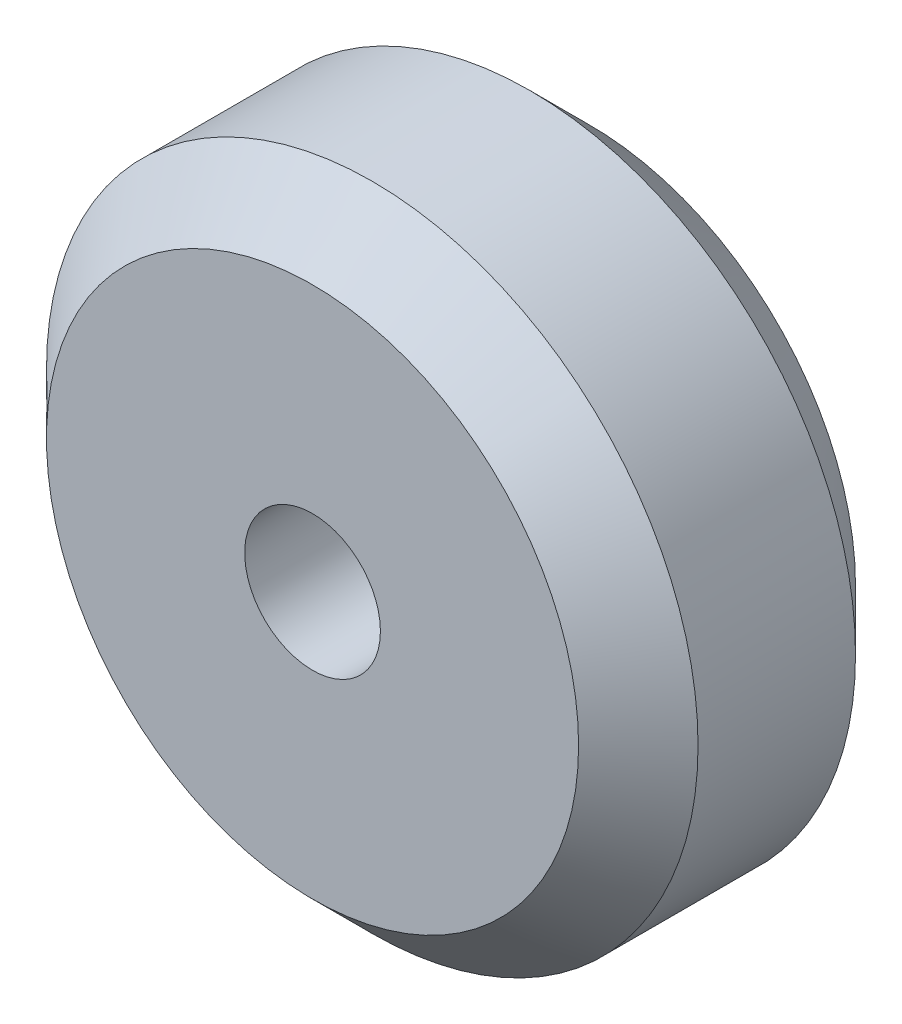
SolidWorks part; units mm, degrees
ref_plane "前视基准面" through (0, 0, 0) normal (0, 0, 1) x (1, 0, 0)
ref_plane "上视基准面" through (0, 0, 0) normal (0, 1, 0) x (1, 0, 0)
ref_plane "右视基准面" through (0, 0, 0) normal (1, 0, 0) x (0, 0, -1)
sketch "草图1" plane through (0, 0, 0) normal (0, 0, 1) x (1, 0, 0)
  circle A0 centre (19.85, -19.85) radius 12
  circle A1 centre (19.85, -19.85) radius 2.5
  dimension "D1" = 24
extrude "凸台-拉伸1" add sketch "草图1" along normal blind 10.2
chamfer "倒角1" distance 2.2 angle 45 2 edges at (31.85, -19.85, 10.2) (31.85, -19.85, 0)
